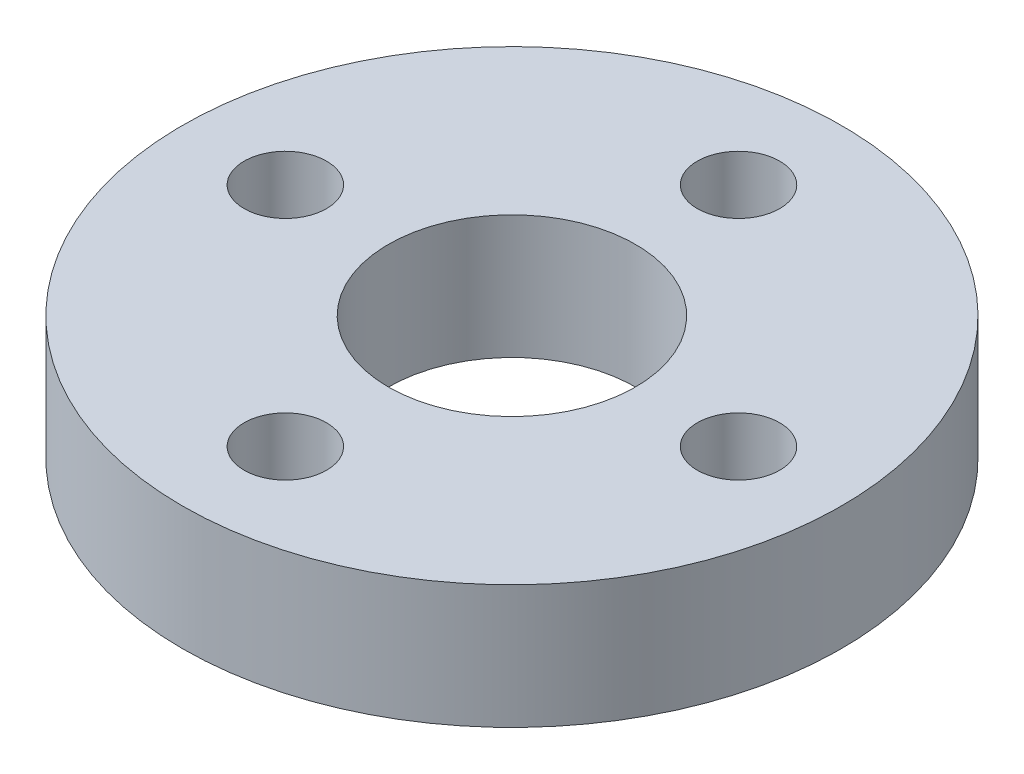
SolidWorks part; units mm, degrees
ref_plane "Front Plane" through (0, 0, 0) normal (0, 0, 1) x (1, 0, 0)
ref_plane "Top Plane" through (0, 0, 0) normal (0, 1, 0) x (1, 0, 0)
ref_plane "Right Plane" through (0, 0, 0) normal (1, 0, 0) x (0, 0, -1)
sketch "Sketch1" plane through (0, 0, 0) normal (0, 1, 0) x (1, 0, 0)
  line L0 (0, 8) -> (0, -8) construction
  circle A0 centre (0, 0) radius 3
  circle A1 centre (0, 0) radius 8
  circle A2 centre (0, 0) radius 5.5 construction
  circle A3 centre (0, 5.5) radius 1
  circle A4 centre (5.5, 0) radius 1
  circle A5 centre (0, -5.5) radius 1
  circle A6 centre (-5.5, 0) radius 1
  point P18 (0, 0)
  dimension "D1" = 6
  dimension "D2" = 16
  dimension "D3" = 2.5
  dimension "D4" = 2
  dimension "D5" = 4
extrude "Boss-Extrude1" add sketch "Sketch1" along normal blind 3
